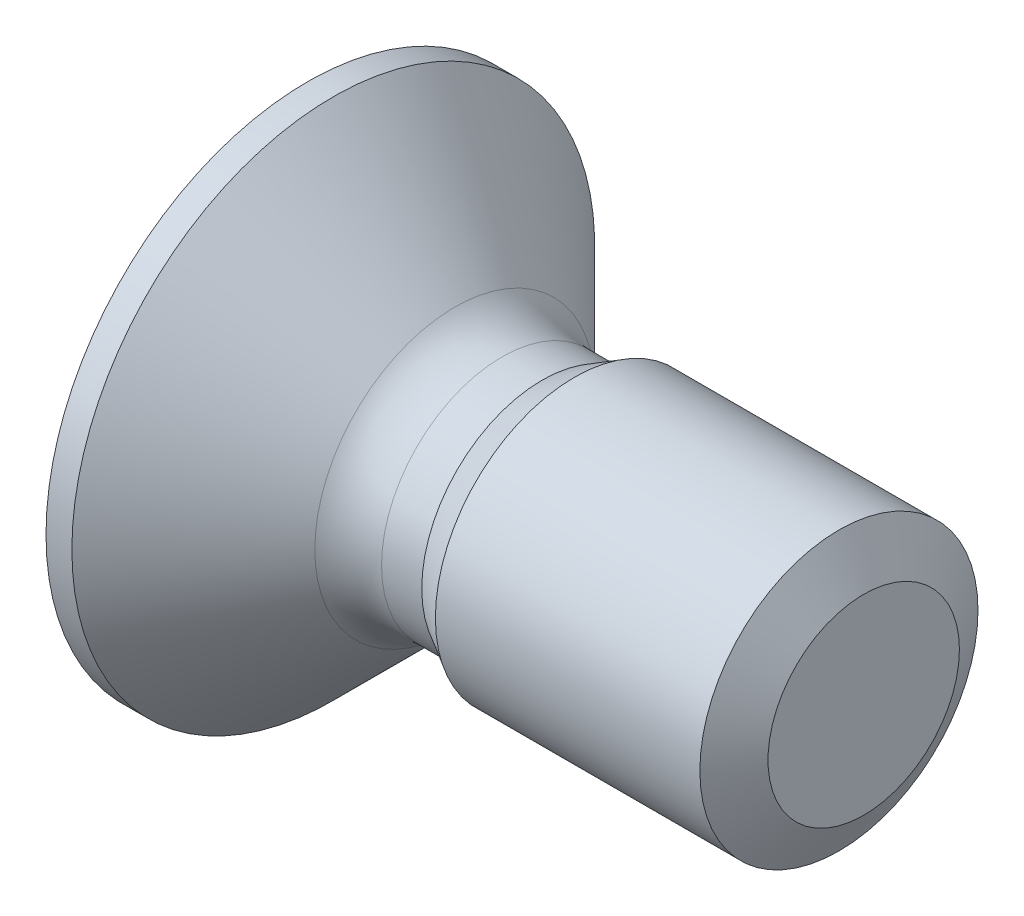
SolidWorks part; units mm, degrees
revolve "基体-旋转" add sketch "草图1" angle 360 about L0
sketch "草图1" plane through (0, 0, 0) normal (0, 0, 1) x (1, 0, 0)
  line L0 (0, 0) -> (4.4175, 0) construction
  line L1 (0, 0) -> (0, 2.35)
  line L2 (0, 2.35) -> (0.2325, 2.35)
  line L3 (0.2325, 2.35) -> (1.3243, 1.2582)
  line L4 (1.7485, 1.0825) -> (2.1099, 1.0825)
  line L5 (2.1099, 1.0825) -> (2.4, 1.25)
  line L6 (2.4, 1.25) -> (5, 1.25)
  line L7 (5, 1.25) -> (5, 0)
  line L8 (0, 0) -> (5, 0)
  arc A0 (1.7485, 1.0825) -> (1.3243, 1.2582) centre (1.7485, 1.6825) cw
  point P12 (1.5, 1.0825)
  dimension "D2" = 0.6
  dimension "D1" = 2.165
  dimension "d" = 2.5
  dimension "dk" = 4.7
  dimension "k" = 1.5
  dimension "D5" = 45
  dimension "a" = 0.9
  dimension "l" = 5
  dimension "D8" = 30
cosmetic thread "装饰螺纹线2" parameters "D1"=2.6, "D2"=2.05
cosmetic thread "装饰螺纹线3" parameters "D1"=2.6676, "D2"=2.013
material "4.8级"
ref_plane "前视" through (0, 0, 0) normal (0, 0, 1) x (1, 0, 0)
ref_plane "上视" through (0, 0, 0) normal (0, 1, 0) x (1, 0, 0)
ref_plane "右视" through (0, 0, 0) normal (1, 0, 0) x (0, 0, -1)
sketch "尺寸草图" plane through (0, 0, 0) normal (0, 0, 1) x (1, 0, 0)
  line L0 (0, 0) -> (5, 0)
  point P3 (1.5, 0)
  point P4 (0.9, 0)
  point P5 (2.5, 0)
  point P6 (4.7, 0)
  point P7 (2.1, 0)
  point P8 (3.5943, 0)
  point P9 (4.4, 0)
  point P10 (3.2, 0)
  point P11 (4.55, 0)
  dimension "d" = 2.5
  dimension "dk" = 4.7
  dimension "k" = 1.5
  dimension "a" = 0.9
  dimension "l" = 5
  dimension "r" = 0.6
  dimension "m" = 2.9
  dimension "h" = 1.8
  dimension "p" = 0.45
sketch "草图2" plane through (0, 0, 0) normal (0, 0, 1) x (1, 0, 0)
  line L0 (4.7774, 1.25) -> (5.2274, 1.25)
  line L1 (5.2274, 1.25) -> (5, 0.8603)
  line L2 (5, 0.8603) -> (4.7774, 1.25)
  line L3 (5, -1.25) -> (5, 1.25) construction
  line L6 (0, 0) -> (-0.4315, 0) construction
  dimension "D1" = 0.45
  dimension "D2" = 0.3897
  dimension "D3" = 1.25
  dimension "D4" = 60
revolve "切除-旋转1" cut sketch "草图2" angle 360 about L6
pattern_linear "阵列(线性)1" [suppressed] count 6 spacing 0.45 along (1, 0, 0)
sketch "草图3" plane through (0, 0, 0) normal (-1, 0, 0) x (0, 0, 1)
  line L0 (0, 0) -> (1.6329, 0) construction
  line L1 (0, 0) -> (0, 0.8499) construction
  line L2 (-1.45, 0.225) -> (1.45, 0.225)
  line L3 (-1.45, 0.225) -> (-1.45, -0.225)
  line L4 (-1.45, -0.225) -> (1.45, -0.225)
  line L5 (1.45, 0.225) -> (1.45, -0.225)
  dimension "m" = 2.9
  dimension "D1" = 0.45
ref_plane "基准面1" through (1.8, 0, 0) normal (-1, 0, 0) x (0, 0, 1)
sketch "草图4" plane through (1.8, 0, 0) normal (-1, 0, 0) x (0, 0, 1)
  point P0 (0, 0)
loft "切除-放样1" cut profiles "草图3", "草图4"
pattern_circular "阵列(圆周)1" count 2 every 90 about axis through (0, 0, 0) along (1, 0, 0) of "切除-放样1"
equation "\"l@草图1\" = \"l@尺寸草图\""
equation "\"k@草图1\" = \"k@尺寸草图\""
equation "\"a@草图1\" = \"a@尺寸草图\""
equation "\"d@草图1\" = \"d@尺寸草图\""
equation "\"dk@草图1\" = \"dk@尺寸草图\""
equation "\"D2@草图1\" = \"r@尺寸草图\""
equation "\"m@草图3\" = \"m@尺寸草图\""
equation "\"h@基准面1\" = \"h@尺寸草图\""
equation "\"D3@阵列(线性)1\" = \"p@尺寸草图\""
equation "\"D3@草图2\" = \"d@草图1\" / 2"
equation "\"D1@装饰螺纹线2\" = \"l@草图1\" - \"k@草图1\" - \"a@草图1\""
equation "\"D2@装饰螺纹线2\" = \"d@尺寸草图\"- \"p@尺寸草图\""
equation "\"D1@阵列(线性)1\" = (  \"l@草图1\" - \"k@草图1\" - \"a@草图1\" )  / \"p@尺寸草图\""
equation "\"D1@草图3\" = \"p@尺寸草图\""
equation "\"D1@草图1\" = \"d@尺寸草图\"*0.866"
equation "\"D2@草图2\" = \"p@尺寸草图\"*0.866"
equation "\"D1@草图2\" = \"p@尺寸草图\""
